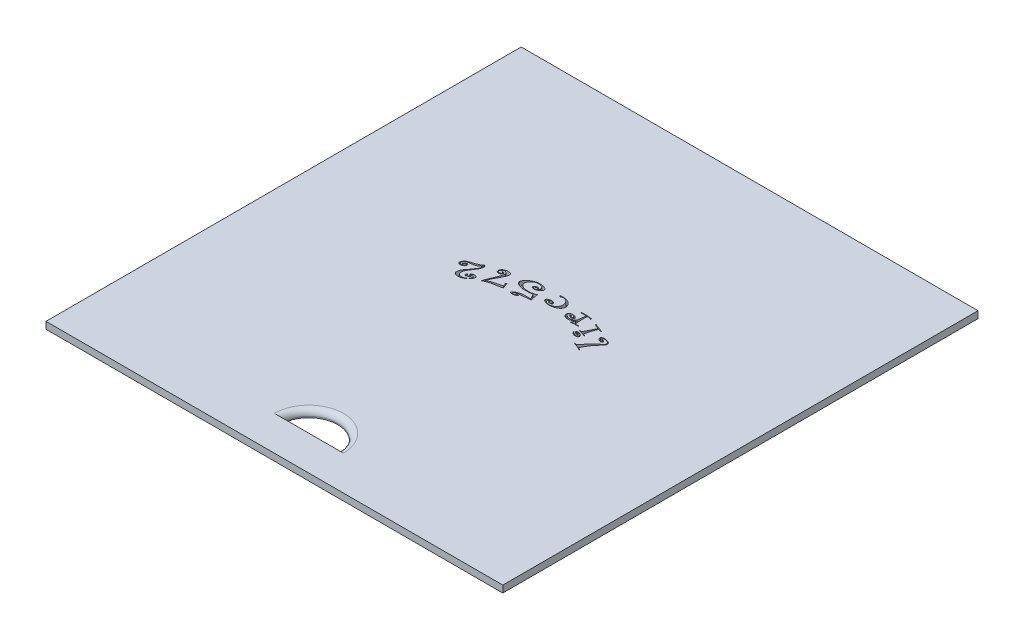
SolidWorks part; units mm, degrees
ref_plane "Front Plane" through (0, 0, 0) normal (0, 0, 1) x (1, 0, 0)
ref_plane "Top Plane" through (0, 0, 0) normal (0, 1, 0) x (1, 0, 0)
ref_plane "Right Plane" through (0, 0, 0) normal (1, 0, 0) x (0, 0, -1)
sketch "Sketch1" plane through (0, 0, 0) normal (0, 1, 0) x (1, 0, 0)
  line L1 (0, 0) -> (79.4, 0)
  line L2 (0, 0) -> (0, 82.6)
  line L3 (0, 82.6) -> (79.4, 82.6)
  line L4 (79.4, 0) -> (79.4, 82.6)
  dimension "D1" = 79.4
  dimension "D2" = 82.6
extrude "Boss-Extrude1" add sketch "Sketch1" along normal blind 1.2
sketch "Sketch2" plane through (0, 1.2, 0) normal (0, 1, 0) x (1, 0, 0)
  line L0 (0, 6) -> (79.4, 6) construction
  line L1 (0, 82.6) -> (0, 0) construction
  line L2 (79.4, 0) -> (79.4, 82.6) construction
  line L3 (0, 0) -> (79.4, 0) construction
  line L4 (34.7, 6) -> (44.7, 6)
  arc A0 (44.7, 6) -> (34.7, 6) centre (39.7, 6) ccw
  dimension "D2" = 10
  dimension "D1" = 6
extrude "Cut-Extrude1" cut sketch "Sketch2" against normal blind 1.2
fillet "Fillet1" radius 1 1 edges at (39.7, 1.2, -11)
sketch "Sketch3" plane through (0, 1.2, 0) normal (0, 1, 0) x (1, 0, 0)
  line L0 (79.4, 41.3) -> (0, 41.3) construction
  line L3 (79.4, 0) -> (79.4, 82.6) construction
  line L4 (0, 82.6) -> (0, 0) construction
  arc A0 (57.7, 41.3) -> (21.7, 41.3) centre (39.7, 23.3) ccw construction
  text T0 "lirc572" font "Curlz MT" height 3.5
  point P9 (39.7, 41.3)
  dimension "D1" = 18
  dimension "D2" = 18
  dimension "D3" = 18
extrude "Cut-Extrude2" cut sketch "Sketch3" against normal blind 0.8
